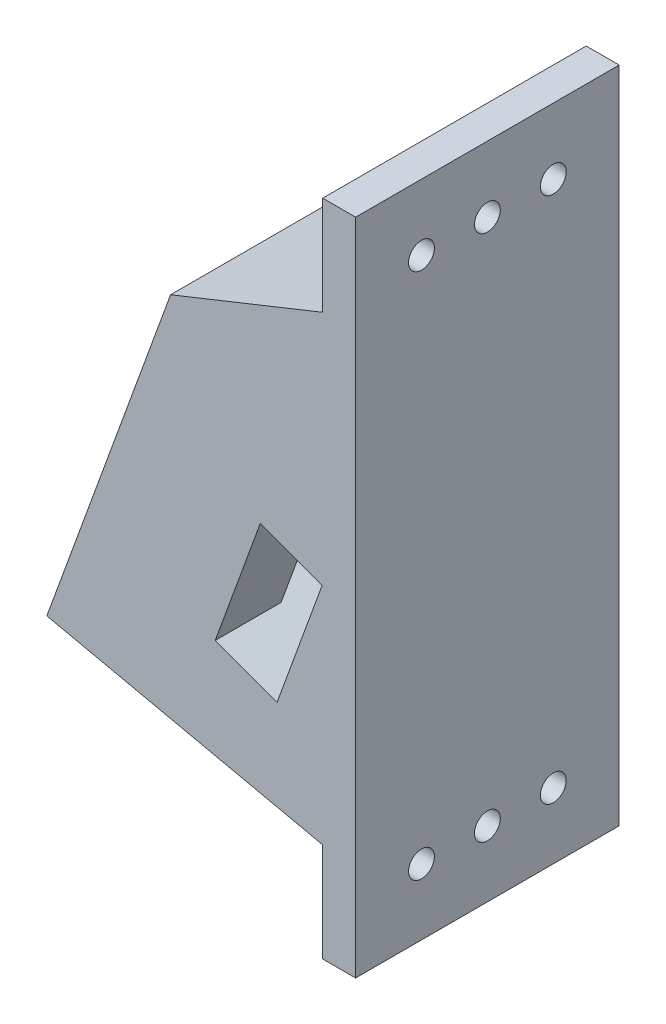
SolidWorks part; units mm, degrees
ref_plane "Front Plane" through (0, 0, 0) normal (0, 0, 1) x (1, 0, 0)
ref_plane "Top Plane" through (0, 0, 0) normal (0, 1, 0) x (1, 0, 0)
ref_plane "Right Plane" through (0, 0, 0) normal (1, 0, 0) x (0, 0, -1)
sketch "Sketch1" plane through (0, 0, 0) normal (0, 0, 1) x (1, 0, 0)
  line L10 (0, 0) -> (0, -95.5816)
  line L16 (0, -95.5816) -> (-6.35, -95.5816)
  line L17 (-6.35, -95.5816) -> (-6.35, -76.5316)
  line L24 (-35.6631, 0.6422) -> (-59.5155, -64.8917)
  line L26 (0, 0) -> (0, 31.4184)
  line L27 (0, 31.4184) -> (-6.35, 31.4184)
  line L28 (-6.35, 31.4184) -> (-6.35, 12.3684)
  line L30 (-6.35, 12.3684) -> (-35.6631, 0.6422)
  line L31 (-6.35, -76.5316) -> (-59.5155, -64.8917)
  dimension "D1" = 6.35
  dimension "D2" = 19.05
  dimension "D4" = 127
  dimension "D6" = 20
extrude "Boss-Extrude1" add sketch "Sketch1" along normal blind 50.8 contours L16 L17 L31 L24 L30 L28 L27 L26 L10
sketch "Sketch3" plane through (-31.6977, 11.537, 0) normal (-0.9397, 0.342, 0) x (0, 0, 1)
  line L0 (25.4, -11.594) -> (25.4, -70.1052) construction
  line L1 (5.4, -68.6338) -> (45.4, -68.6338)
  line L2 (5.4, -68.6338) -> (5.4, -23.6338)
  line L3 (5.4, -23.6338) -> (45.4, -23.6338)
  line L4 (45.4, -68.6338) -> (45.4, -23.6338)
  line L5 (5.4, -68.6338) -> (45.4, -23.6338) construction
  line L6 (5.4, -23.6338) -> (45.4, -68.6338) construction
  line L7 (50.8, -11.594) -> (0, -11.594) construction
  line L9 (50.8, -81.3338) -> (0, -81.3338) construction
  point P0 (25.4, -46.1338)
  dimension "D1" = 40
  dimension "D2" = 45
  dimension "D3" = 12.7
extrude "Cut-Extrude1" cut sketch "Sketch3" against normal blind 20
sketch "Sketch4" plane through (-31.6977, 11.537, 0) normal (-0.9397, 0.342, 0) x (0, 0, 1)
  line L0 (5.4, -23.6338) -> (45.4, -23.6338) construction
  line L1 (5.4, -68.6338) -> (45.4, -68.6338) construction
  circle A2 centre (25.4, -17.2838) radius 2.4892
  circle A3 centre (25.4, -74.9838) radius 2.4892
  dimension "D1" = 4.9784
  dimension "D2" = 6.35
  dimension "D3" = 6.35
extrude "Cut-Extrude2" cut sketch "Sketch4" against normal blind 17.78 contours A2 | A3
sketch "Sketch7" plane through (-12.9039, 4.6966, 0) normal (-0.9397, 0.342, 0) x (0, 0, 1)
  line L0 (45.4, -23.6338) -> (5.4, -68.6338) construction
  line L1 (12.7, -58.8338) -> (38.1, -58.8338)
  line L2 (12.7, -58.8338) -> (12.7, -33.4338)
  line L3 (12.7, -33.4338) -> (38.1, -33.4338)
  line L4 (38.1, -58.8338) -> (38.1, -33.4338)
  line L5 (12.7, -58.8338) -> (38.1, -33.4338) construction
  line L6 (12.7, -33.4338) -> (38.1, -58.8338) construction
  line L7 (5.4, -23.6338) -> (45.4, -68.6338) construction
  point P0 (25.4, -46.1338)
  point P14 (25.4, -46.1338)
  dimension "D1" = 25.4
  dimension "D2" = 25.4
extrude "Cut-Extrude3" cut sketch "Sketch7" against normal blind 19.05
sketch "Sketch9" plane through (0, 0, 38.1) normal (0, 0, -1) x (-1, 0, 0)
  line L0 (6.4378, -33.2363) -> (15.1251, -57.1045)
  line L5 (6.4378, -33.2363) -> (18.3719, -28.8927)
  line L6 (15.1251, -57.1045) -> (27.0592, -52.7609)
  line L7 (18.3719, -28.8927) -> (27.0592, -52.7609)
  dimension "D1" = 12.7
extrude "Cut-Extrude4" cut sketch "Sketch9" against normal through all and the other way through all
sketch "Sketch10" plane through (-6.35, 0, 0) normal (-1, 0, 0) x (0, 0, 1)
  line L0 (50.8, 31.4184) -> (0, 31.4184) construction
  line L1 (50.8, -95.5816) -> (0, -95.5816) construction
  line L2 (25.4, 31.4184) -> (25.4, 12.3684) construction
  line L3 (50.8, 12.3684) -> (0, 12.3684) construction
  circle A0 centre (25.4, 18.7184) radius 2.4892
  circle A1 centre (12.7, 18.7184) radius 2.4892
  circle A2 centre (12.7, -82.8816) radius 2.4892
  circle A3 centre (38.1, -82.8816) radius 2.4892
  circle A4 centre (38.1, 18.7184) radius 2.4892
  circle A5 centre (25.4, -82.8816) radius 2.4892
  dimension "D1" = 4.9784
  dimension "D2" = 12.7
  dimension "D3" = 12.7
  dimension "D4" = 12.7
  dimension "D5" = 12.7
extrude "Cut-Extrude5" cut sketch "Sketch10" against normal through all
sketch "Sketch11" plane through (-12.9039, 4.6966, 0) normal (-0.9397, 0.342, 0) x (0, 0, 1)
  line L0 (5.4, -23.6338) -> (45.4, -23.6338) construction
  line L1 (5.4, -68.6338) -> (5.4, -23.6338) construction
  line L2 (25.4, -11.594) -> (25.4, -70.1052) construction
  line L3 (25.4, -11.594) -> (25.4, -70.1052) construction
  line L4 (5.4, -46.1338) -> (45.4, -46.1338) construction
  line L5 (45.4, -68.6338) -> (45.4, -23.6338) construction
  circle A0 centre (10.48, -28.7138) radius 2.54
  circle A1 centre (40.32, -28.7138) radius 2.54
  circle A2 centre (40.32, -63.5538) radius 2.54
  circle A3 centre (10.48, -63.5538) radius 2.54
  dimension "D1" = 5.08
  dimension "D2" = 5.08
  dimension "D3" = 5.08
extrude "Boss-Extrude2" add sketch "Sketch11" along normal blind 5.08
